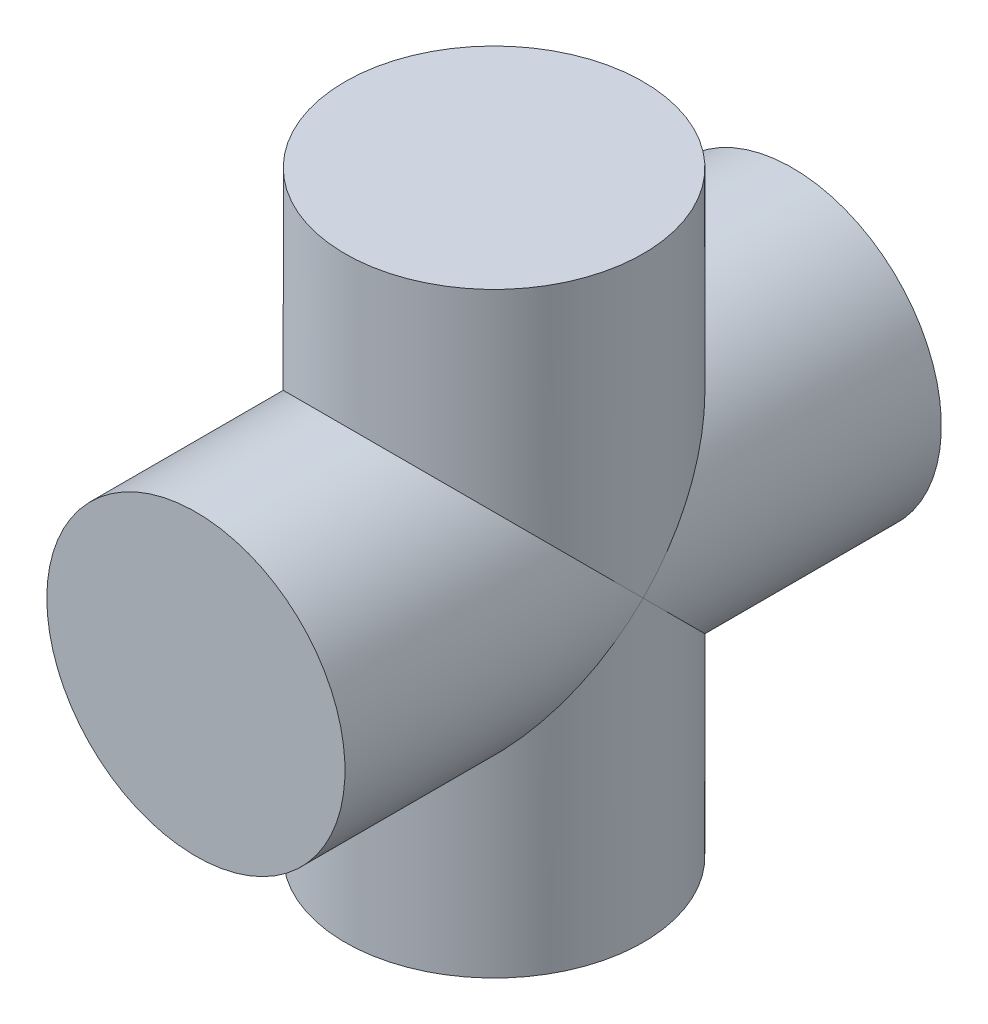
SolidWorks part; units mm, degrees
ref_plane "Płaszczyzna przednia" through (0, 0, 0) normal (0, 0, 1) x (1, 0, 0)
ref_plane "Płaszczyzna górna" through (0, 0, 0) normal (0, 1, 0) x (1, 0, 0)
ref_plane "Płaszczyzna prawa" through (0, 0, 0) normal (1, 0, 0) x (0, 0, -1)
sketch "Szkic1" plane through (0, 0, 0) normal (0, 0, 1) x (1, 0, 0)
  line L1 (0, 20) -> (-10, 20)
  line L2 (0, 20) -> (0, -20)
  line L3 (0, -20) -> (-10, -20)
  line L4 (-10, 20) -> (-10, -20)
  point P4 (0, 0)
  dimension "D1" = 40
  dimension "D2" = 10
revolve "Obrót1" add sketch "Szkic1" angle 360 about L2
sketch "Szkic2" plane through (0, 0, 0) normal (0, 1, 0) x (1, 0, 0)
  line L1 (-10, 20) -> (0, 20)
  line L2 (-10, 20) -> (-10, -20)
  line L3 (-10, -20) -> (0, -20)
  line L4 (0, 20) -> (0, -20)
  point P4 (0, 0)
  dimension "D1" = 40
  dimension "D2" = 10
revolve "Obrót2" add sketch "Szkic2" angle 360 about L4
